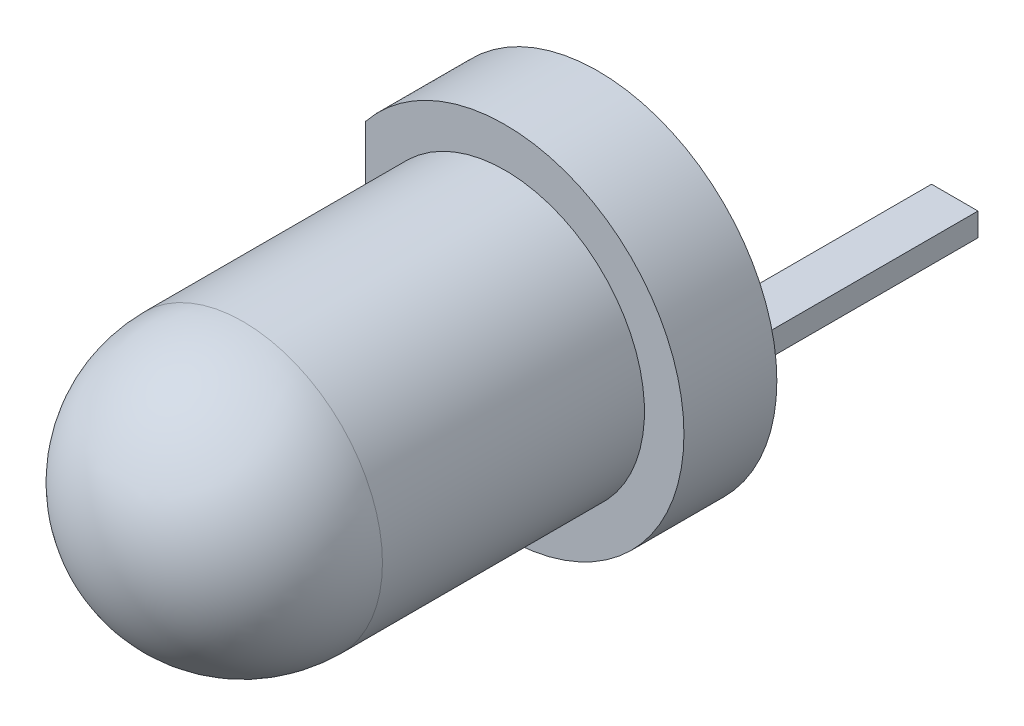
SolidWorks part; units mm, degrees
ref_plane "Plano frontal" through (0, 0, 0) normal (0, 0, 1) x (1, 0, 0)
ref_plane "Plano superior" through (0, 0, 0) normal (0, 1, 0) x (1, 0, 0)
ref_plane "Plano direito" through (0, 0, 0) normal (1, 0, 0) x (0, 0, -1)
sketch "Esboço1" plane through (0, 0, 0) normal (0, 0, 1) x (1, 0, 0)
  circle A0 centre (0, 0) radius 1.5
  dimension "D1" = 3
extrude "Ressalto-extrusão1" add sketch "Esboço1" along normal blind 5.32
fillet "Filete1" radius 1.5 1 edges at (1.5, 0, 5.32)
sketch "Esboço2" plane through (0, 0, 0) normal (0, 0, -1) x (-1, 0, 0)
  line L0 (1.5, -1.2065) -> (1.5, 1.2065)
  arc A0 (1.5, 1.2065) -> (1.5, -1.2065) centre (0, 0) ccw
  dimension "D1" = 3.85
extrude "Ressalto-extrusão2" add sketch "Esboço2" against normal blind 1
sketch "Esboço3" plane through (0, 0, 0) normal (0, 0, -1) x (-1, 0, 0)
  line L0 (0, 0) -> (-1.3, 0) construction
  line L2 (-1.55, 0.125) -> (-1.05, 0.125)
  line L3 (-1.55, 0.125) -> (-1.55, -0.125)
  line L4 (1.24, 0) -> (0, 0) construction
  line L5 (-1.55, -0.125) -> (-1.05, -0.125)
  line L6 (-1.05, 0.125) -> (-1.05, -0.125)
  line L7 (-1.55, 0.125) -> (-1.05, -0.125) construction
  line L8 (-1.55, -0.125) -> (-1.05, 0.125) construction
  line L9 (1.49, -0.125) -> (0.99, -0.125)
  line L10 (1.49, -0.125) -> (1.49, 0.125)
  line L11 (1.49, 0.125) -> (0.99, 0.125)
  line L12 (0.99, -0.125) -> (0.99, 0.125)
  line L13 (1.49, -0.125) -> (0.99, 0.125) construction
  line L14 (1.49, 0.125) -> (0.99, -0.125) construction
  dimension "D1" = 0.5
  dimension "D2" = 0.5
  dimension "D3" = 0.25
  dimension "D4" = 0.25
  dimension "D5" = 1.3
  dimension "D6" = 1.24
extrude "Ressalto-extrusão3" add sketch "Esboço3" along normal blind 2.54
sketch "Esboço4" plane through (0, 0, -2.54) normal (0, 0, -1) x (-1, 0, 0)
  line L1 (0.7638, 0.2582) -> (1.6997, 0.2582)
  line L2 (0.7638, 0.2582) -> (0.7638, -0.234)
  line L3 (0.7638, -0.234) -> (1.6997, -0.234)
  line L4 (1.6997, 0.2582) -> (1.6997, -0.234)
extrude "Corte-extrusão1" cut sketch "Esboço4" against normal blind 1
